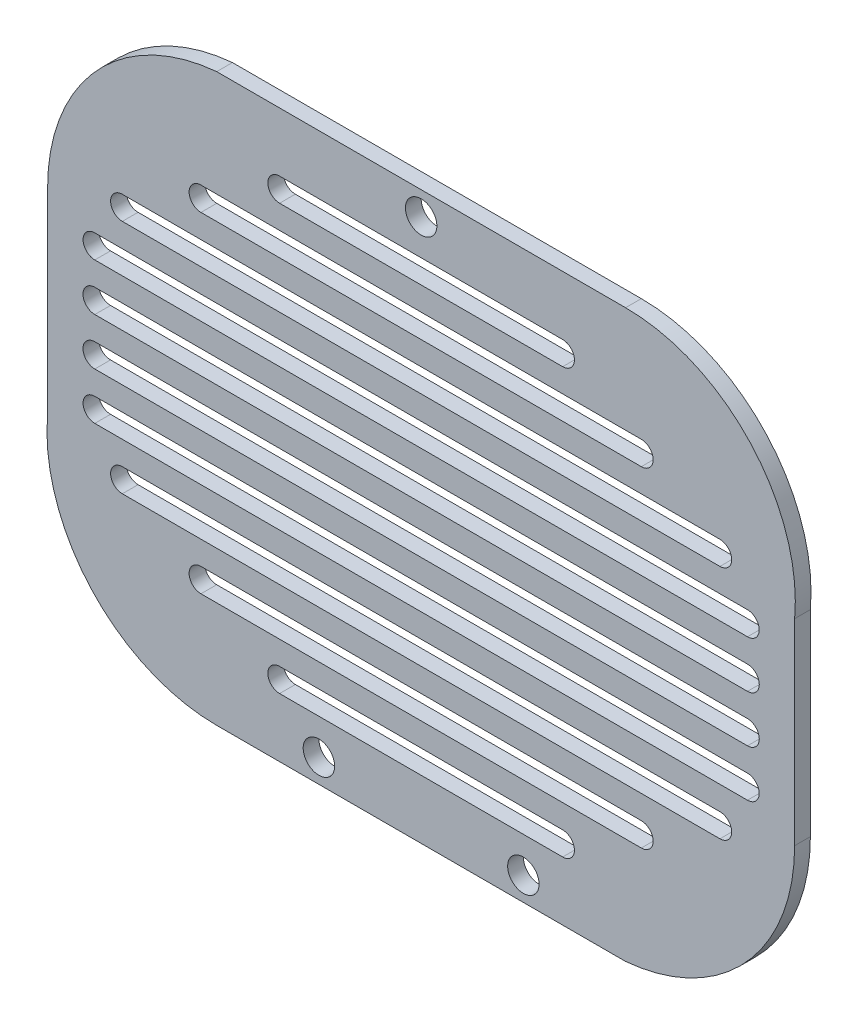
SolidWorks part; units mm, degrees
ref_plane "Front Plane" through (0, 0, 0) normal (0, 0, 1) x (1, 0, 0)
ref_plane "Top Plane" through (0, 0, 0) normal (0, 1, 0) x (1, 0, 0)
ref_plane "Right Plane" through (0, 0, 0) normal (1, 0, 0) x (0, 0, -1)
sketch "Sketch1" plane through (0, 0, 0) normal (0, 0, 1) x (1, 0, 0)
  line L1 (-47.5, -12.5) -> (47.5, -12.5)
  line L2 (-47.5, -12.5) -> (-47.5, 12.5)
  line L3 (-47.5, 12.5) -> (47.5, 12.5)
  line L4 (47.5, -12.5) -> (47.5, 12.5)
  line L5 (-47.5, -12.5) -> (47.5, 12.5) construction
  line L6 (-47.5, 12.5) -> (47.5, -12.5) construction
  line L7 (26, -36) -> (-26, -36)
  line L8 (26, -36) -> (26, 36)
  line L9 (26, 36) -> (-26, 36)
  line L10 (-26, -36) -> (-26, 36)
  line L11 (26, -36) -> (-26, 36) construction
  line L12 (26, 36) -> (-26, -36) construction
  arc A0 (-47.5, 12.5) -> (-26, 36) centre (-23.907, 12.5) cw
  arc A1 (26, 36) -> (47.5, 12.5) centre (26, 14.4149) cw
  arc A2 (47.5, -12.5) -> (26, -36) centre (23.907, -12.5) cw
  arc A3 (-26, -36) -> (-47.5, -12.5) centre (-26, -14.4149) cw
  point P0 (0, 0)
  point P6 (0, 0)
extrude "Boss-Extrude1" add sketch "Sketch1" along normal blind 2 contours L10 L3 L8 L9 | A1 L8 L3 | L8 L1 L4 L3 | L10 L1 L8 L3 | A2 L1 L8 | L10 L7 L8 L1 | A3 L10 L1 | L1 L10 L3 L2 | A0 L3 L10
sketch "Sketch2" plane through (0, 0, 2) normal (0, 0, 1) x (1, 0, 0)
  line L0 (-47.5, 0) -> (47.5, 0)
  line L1 (-47.5, -12.5) -> (-47.5, 12.5) construction
  line L2 (47.5, -12.5) -> (47.5, 12.5) construction
  line L3 (0, 0) -> (0, -1.5)
  line L4 (0, -1.5) -> (41.5, -1.5)
  line L5 (0, -1.5) -> (-41.5, -1.5)
  line L6 (-18, 25.5) -> (0, 25.5)
  line L7 (-41.5, -4.5) -> (41.5, -4.5)
  line L8 (18, 28.5) -> (-18, 28.5)
  line L9 (0, 25.5) -> (18, 25.5)
  line L10 (0, -7.5) -> (41.5, -7.5)
  line L11 (0, 22.5) -> (0, 25.5)
  line L12 (41.5, -10.5) -> (-41.5, -10.5)
  line L13 (-28, 19.5) -> (0, 19.5)
  line L14 (-41.5, -7.5) -> (0, -7.5)
  line L15 (28, 22.5) -> (-28, 22.5)
  line L16 (0, -13.5) -> (38, -13.5)
  line L17 (0, 19.5) -> (28, 19.5)
  line L18 (38, -16.5) -> (-38, -16.5)
  line L19 (-38, 13.5) -> (0, 13.5)
  line L20 (-38, -13.5) -> (0, -13.5)
  line L21 (38, 16.5) -> (-38, 16.5)
  line L22 (0, -19.5) -> (28, -19.5)
  line L23 (0, 13.5) -> (38, 13.5)
  line L24 (28, -22.5) -> (-28, -22.5)
  line L25 (-41.5, 7.5) -> (0, 7.5)
  line L26 (-28, -19.5) -> (0, -19.5)
  line L27 (0, -22.5) -> (0, -25.5)
  line L28 (0, -25.5) -> (18, -25.5)
  line L29 (41.5, 10.5) -> (-41.5, 10.5)
  line L30 (18, -28.5) -> (-18, -28.5)
  line L31 (0, 7.5) -> (41.5, 7.5)
  line L32 (-18, -25.5) -> (0, -25.5)
  line L33 (-41.5, 4.5) -> (41.5, 4.5)
  line L34 (0, 1.5) -> (-41.5, 1.5)
  line L35 (0, 1.5) -> (41.5, 1.5)
  line L36 (-41.5, -3) -> (41.5, -3) construction
  line L37 (-18, 27) -> (18, 27) construction
  line L38 (-41.5, -1.4996) -> (41.5, -1.4996)
  line L39 (-18, 25.5044) -> (18, 25.5044)
  line L40 (-41.5, -4.5004) -> (41.5, -4.5004)
  line L41 (-41.5, -9) -> (41.5, -9) construction
  line L42 (-41.5, -7.5095) -> (41.5, -7.5095)
  line L43 (-41.5, -10.4905) -> (41.5, -10.4905)
  line L44 (-38, -15) -> (38, -15) construction
  line L45 (-38, -13.5078) -> (38, -13.5078)
  line L46 (-38, -16.4922) -> (38, -16.4922)
  line L47 (-28, -21) -> (28, -21) construction
  line L48 (-28, -19.4937) -> (28, -19.4937)
  line L49 (-28, -22.5063) -> (28, -22.5063)
  line L50 (-18, -27) -> (18, -27) construction
  line L51 (-18, -25.5044) -> (18, -25.5044)
  line L52 (-18, -28.4956) -> (18, -28.4956)
  line L53 (-18, 28.4956) -> (18, 28.4956)
  line L54 (-28, 21) -> (28, 21) construction
  line L55 (-28, 19.4937) -> (28, 19.4937)
  line L56 (-28, 22.5063) -> (28, 22.5063)
  line L57 (-38, 15) -> (38, 15) construction
  line L58 (-38, 13.5078) -> (38, 13.5078)
  line L59 (-38, 16.4922) -> (38, 16.4922)
  line L60 (-41.5, 9) -> (41.5, 9) construction
  line L61 (-41.5, 7.5095) -> (41.5, 7.5095)
  line L62 (-41.5, 10.4905) -> (41.5, 10.4905)
  line L63 (-41.5, 3) -> (41.5, 3) construction
  line L64 (-41.5, 1.4996) -> (41.5, 1.4996)
  line L65 (-41.5, 4.5004) -> (41.5, 4.5004)
  arc A0 (-41.5, -1.4996) -> (-41.5, -4.5004) centre (-41.5, -3) ccw
  arc A1 (41.5, -4.5004) -> (41.5, -1.4996) centre (41.5, -3) ccw
  arc A2 (-41.5, -7.5095) -> (-41.5, -10.4905) centre (-41.5, -9) ccw
  arc A3 (41.5, -10.4905) -> (41.5, -7.5095) centre (41.5, -9) ccw
  arc A4 (-38, -13.5078) -> (-38, -16.4922) centre (-38, -15) ccw
  arc A5 (38, -16.4922) -> (38, -13.5078) centre (38, -15) ccw
  arc A6 (-28, -19.4937) -> (-28, -22.5063) centre (-28, -21) ccw
  arc A7 (28, -22.5063) -> (28, -19.4937) centre (28, -21) ccw
  arc A8 (-18, -25.5044) -> (-18, -28.4956) centre (-18, -27) ccw
  arc A9 (18, -28.4956) -> (18, -25.5044) centre (18, -27) ccw
  arc A10 (-18, 25.5044) -> (-18, 28.4956) centre (-18, 27) cw
  arc A11 (18, 28.4956) -> (18, 25.5044) centre (18, 27) cw
  arc A12 (-28, 19.4937) -> (-28, 22.5063) centre (-28, 21) cw
  arc A13 (28, 22.5063) -> (28, 19.4937) centre (28, 21) cw
  arc A14 (-38, 13.5078) -> (-38, 16.4922) centre (-38, 15) cw
  arc A15 (38, 16.4922) -> (38, 13.5078) centre (38, 15) cw
  arc A16 (-41.5, 7.5095) -> (-41.5, 10.4905) centre (-41.5, 9) cw
  arc A17 (41.5, 10.4905) -> (41.5, 7.5095) centre (41.5, 9) cw
  arc A18 (-41.5, 1.4996) -> (-41.5, 4.5004) centre (-41.5, 3) cw
  arc A19 (41.5, 4.5004) -> (41.5, 1.4996) centre (41.5, 3) cw
  point P43 (0, -3)
  point P52 (0, -9)
  point P57 (0, -15)
  point P62 (0, -21)
  point P67 (0, -27)
  point P97 (0, 27)
  point P104 (0, 21)
  point P111 (0, 15)
  point P118 (0, 9)
  point P125 (0, 3)
extrude "Cut-Extrude1" cut sketch "Sketch2" against normal blind 2
sketch "Sketch3" plane through (0, 0, 2) normal (0, 0, 1) x (1, 0, 0)
  line L0 (0, 0) -> (0, 33)
  line L1 (0, 0) -> (0, -33)
  line L3 (0, -33) -> (13, -33)
  line L4 (0, -33) -> (-13, -33)
  circle A0 centre (0, 33) radius 2
  circle A1 centre (-13, -33) radius 2
  circle A2 centre (13, -33) radius 2
extrude "Cut-Extrude2" cut sketch "Sketch3" against normal blind 10
sketch "Sketch4" plane through (0, 0, 2) normal (0, 0, 1) x (1, 0, 0)
  line L0 (0, 33) -> (0, -32.9954)
  line L1 (0, -32.9954) -> (13, -33)
